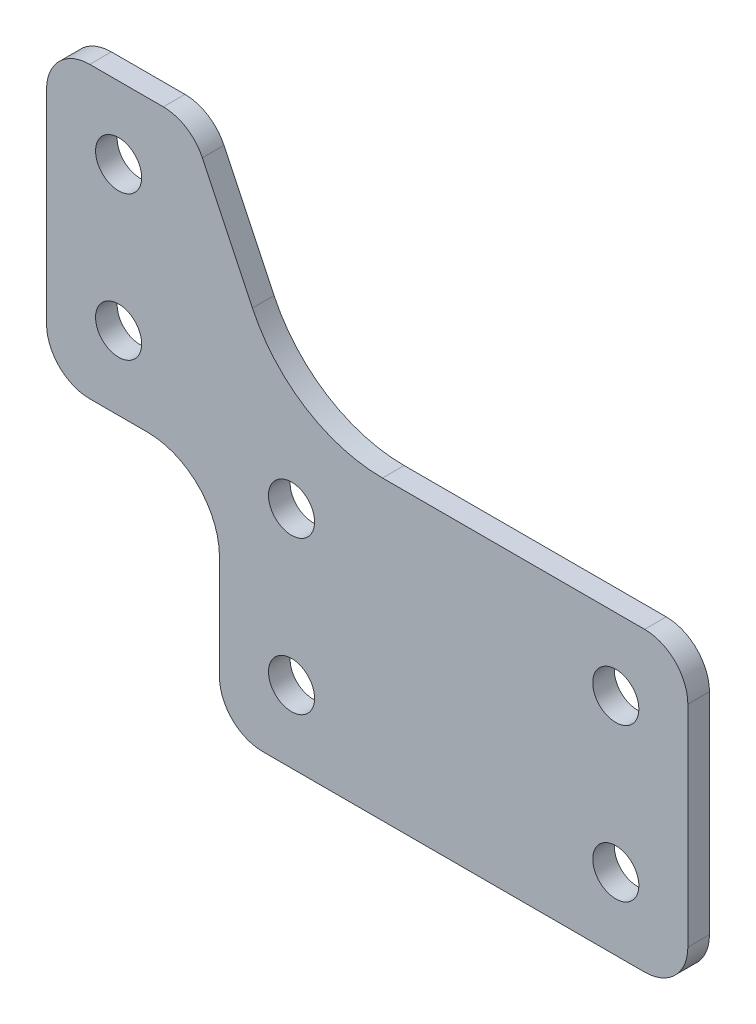
SolidWorks part; units mm, degrees
material "5052-H34"
ref_plane "正面" through (0, 0, 0) normal (0, 0, 1) x (1, 0, 0)
ref_plane "平面" through (0, 0, 0) normal (0, 1, 0) x (1, 0, 0)
ref_plane "右側面" through (0, 0, 0) normal (1, 0, 0) x (0, 0, -1)
sketch "ｽｹｯﾁ1" plane through (0, 0, 0) normal (0, 0, 1) x (1, 0, 0)
  line L0 (0, 0) -> (0, 5.3) construction
  line L1 (11.25, 5.3) -> (-11.25, 5.3) construction
  line L2 (11.25, 5.3) -> (11.25, -5.3) construction
  line L3 (11.25, -5.3) -> (-11.25, -5.3) construction
  line L4 (-11.25, 5.3) -> (-11.25, -5.3) construction
  line L5 (11.25, 5.3) -> (-11.25, -5.3) construction
  line L6 (11.25, -5.3) -> (-11.25, 5.3) construction
  line L7 (11.25, 5.3) -> (11.25, -5.3)
  line L8 (0, 0) -> (-23.25, 0) construction
  line L9 (16.25, 10.3) -> (-16.25, 10.3)
  line L10 (16.25, 10.3) -> (16.25, -10.3)
  line L11 (16.25, -10.3) -> (-16.25, -10.3)
  line L12 (-16.25, 10.3) -> (-16.25, -10.3)
  line L13 (16.25, 10.3) -> (-16.25, -10.3) construction
  line L14 (16.25, -10.3) -> (-16.25, 10.3) construction
  line L15 (-23.25, 0) -> (-23.25, 20) construction
  line L16 (-23.25, 20) -> (-23.25, 10) construction
  line L17 (-18.25, 25) -> (-11.25, 10.3)
  line L18 (-18.25, 25) -> (-28.25, 25)
  line L19 (-18.25, 25) -> (-18.25, 5)
  line L20 (-18.25, 5) -> (-28.25, 5)
  line L21 (-28.25, 25) -> (-28.25, 5)
  line L22 (-18.25, 25) -> (-28.25, 5) construction
  line L23 (-18.25, 5) -> (-28.25, 25) construction
  line L24 (-28.25, 5) -> (-28.25, 4.9)
  line L25 (-28.25, 4.9) -> (-16.25, 4.9)
  circle A0 centre (-11.25, 5.3) radius 1.6
  circle A1 centre (-11.25, -5.3) radius 1.6
  circle A2 centre (11.25, -5.3) radius 1.6
  circle A3 centre (11.25, 5.3) radius 1.6
  circle A4 centre (-23.25, 20) radius 1.6
  circle A5 centre (-23.25, 10) radius 1.6
  point P0 (0, 0)
  point P21 (-23.25, 15)
  dimension "D3" = 3.2
  dimension "D6" = 10
  dimension "D7" = 10
  dimension "D1" = 10.6
  dimension "D2" = 22.5
  dimension "D4" = 5
  dimension "D5" = 5
  dimension "D8" = 7
  dimension "D9" = 5
  dimension "D10" = 5
  dimension "D11" = 0.1
  dimension "D12" = 5
extrude "ﾎﾞｽ - 押し出し1" add sketch "ｽｹｯﾁ1" along normal blind 1.5
fillet "ﾌｨﾚｯﾄ5" radius 3 6 edges at (-16.25, -10.3, 0.75) (16.25, -10.3, 0.75) (16.25, 10.3, 0.75) (-28.25, 25, 0.75) (-28.25, 4.9, 0.75) (-18.25, 25, 0.75)
fillet "ﾌｨﾚｯﾄ6" radius 5 1 edges at (-16.25, 4.9, 0.75)
fillet "ﾌｨﾚｯﾄ8" radius 10 1 edges at (-11.25, 10.3, 0.75)
